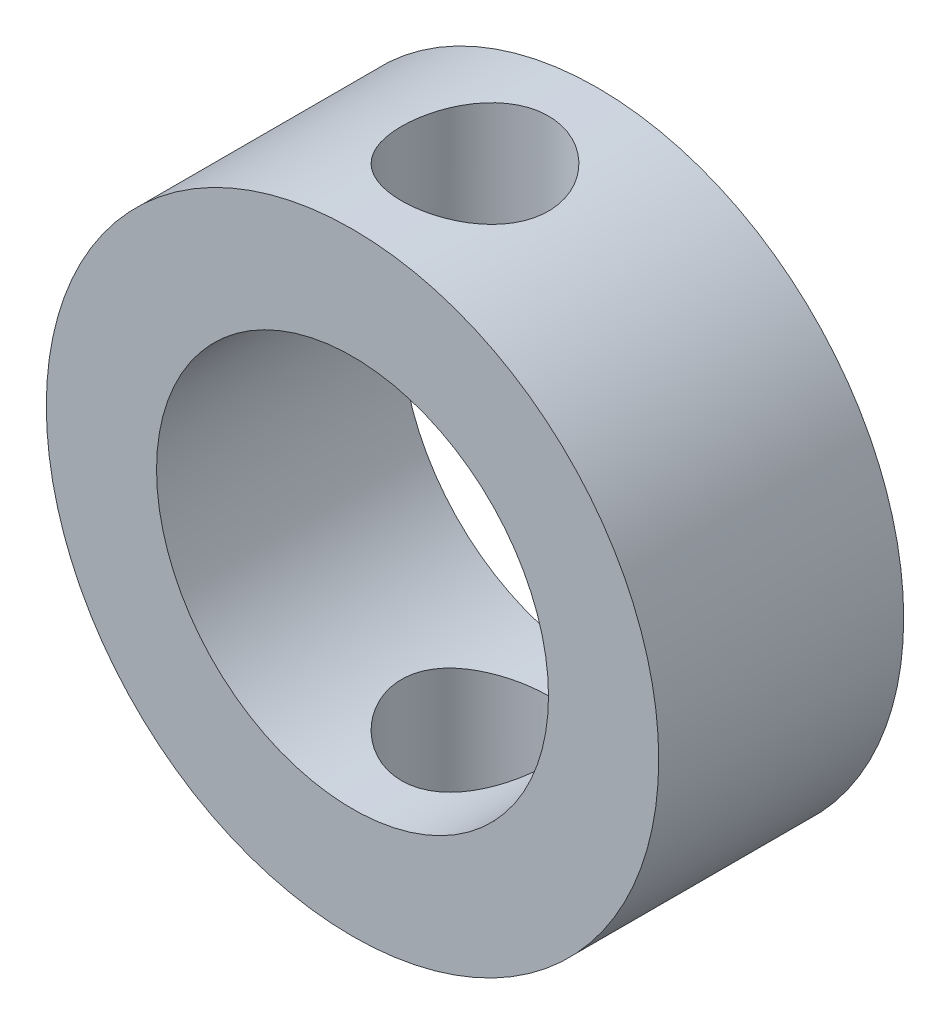
SolidWorks part; units mm, degrees
ref_plane "Front Plane" through (0, 0, 0) normal (0, 0, 1) x (1, 0, 0)
ref_plane "Top Plane" through (0, 0, 0) normal (0, 1, 0) x (1, 0, 0)
ref_plane "Right Plane" through (0, 0, 0) normal (1, 0, 0) x (0, 0, -1)
sketch "Sketch1" plane through (0, 0, 0) normal (0, 0, 1) x (1, 0, 0)
  line L0 (0, 56.6654) -> (0, -56.6654) construction
  line L1 (-84.0565, 0) -> (84.0565, 0) construction
  circle A0 centre (0, 0) radius 8
  circle A1 centre (0, 0) radius 12.5
  point P4 (0, 0)
  point P7 (0, 0)
  dimension "D1" = 25
  dimension "D2" = 16
extrude "Boss-Extrude1" add sketch "Sketch1" along normal mid plane 10
sketch "Sketch2" plane through (0, 0, 0) normal (0, 1, 0) x (1, 0, 0)
  circle A0 centre (0, 0) radius 3
  dimension "D1" = 6
extrude "Cut-Extrude1" cut sketch "Sketch2" against normal mid plane 50
